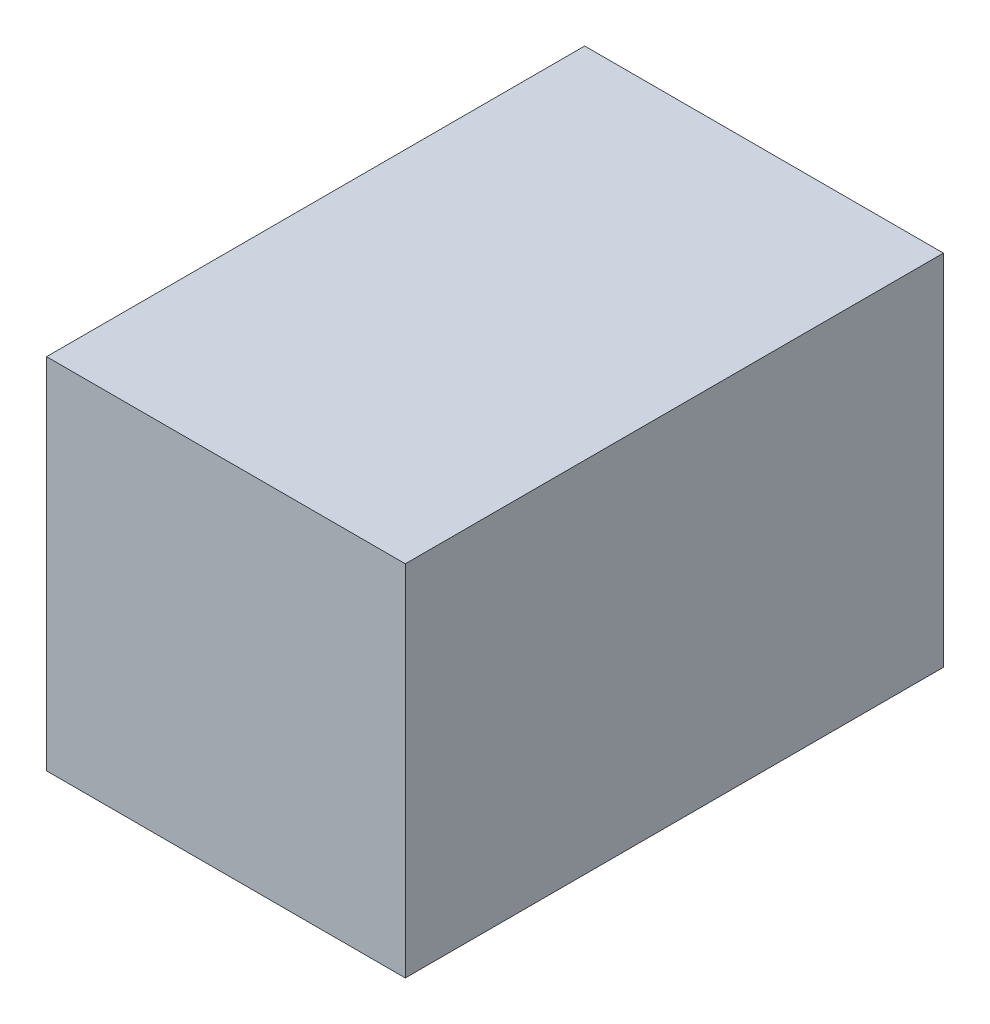
SolidWorks part; units mm, degrees
ref_plane "Front Plane" through (0, 0, 0) normal (0, 0, 1) x (1, 0, 0)
ref_plane "Top Plane" through (0, 0, 0) normal (0, 1, 0) x (1, 0, 0)
ref_plane "Right Plane" through (0, 0, 0) normal (1, 0, 0) x (0, 0, -1)
sketch "Sketch1" plane through (0, 0, 0) normal (0, 1, 0) x (1, 0, 0)
  line L1 (-6.35, 9.525) -> (6.35, 9.525)
  line L2 (-6.35, 9.525) -> (-6.35, -9.525)
  line L3 (-6.35, -9.525) -> (6.35, -9.525)
  line L4 (6.35, 9.525) -> (6.35, -9.525)
  line L5 (-6.35, 9.525) -> (6.35, -9.525) construction
  line L6 (-6.35, -9.525) -> (6.35, 9.525) construction
  point P0 (0, 0)
  point P6 (19.05, 28.8491)
  dimension "D1" = 12.7
  dimension "D2" = 19.05
extrude "Boss-Extrude1" add sketch "Sketch1" along normal blind 12.7
sketch "Sketch2" plane through (0, 12.7, 0) normal (0, 1, 0) x (1, 0, 0)
  line L3 (-12.7, -9.525) -> (12.7, -9.525)
  line L9 (6.35, 9.525) -> (-6.35, 9.525) construction
  point P9 (-11.5026, 5.1381)
  point P10 (-12.3623, 0.6964)
  point P13 (-12.7, 0.4815)
  dimension "D4" = 19.05
